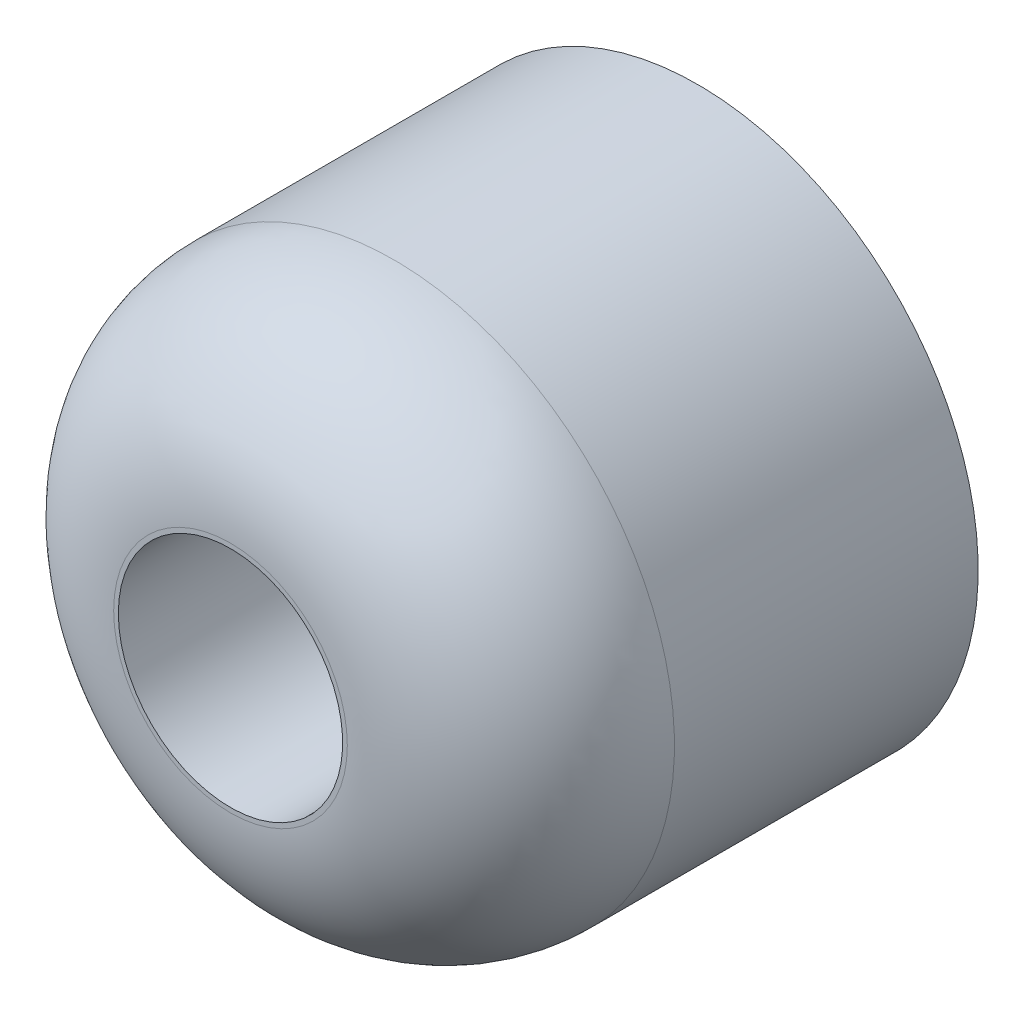
SolidWorks part; units mm, degrees
ref_plane "Front Plane" through (0, 0, 0) normal (0, 0, 1) x (1, 0, 0)
ref_plane "Top Plane" through (0, 0, 0) normal (0, 1, 0) x (1, 0, 0)
ref_plane "Right Plane" through (0, 0, 0) normal (1, 0, 0) x (0, 0, -1)
sketch "Sketch1" plane through (0, 0, 0) normal (1, 0, 0) x (0, 0, -1)
  line L0 (0, 0) -> (-21.5788, 0) construction
  line L1 (0, 2.4) -> (-10, 2.4)
  line L2 (-10, 2.4) -> (-10, 2.5)
  line L3 (-6.5, 6) -> (0, 6)
  line L4 (0, 6) -> (0, 5.5)
  line L5 (0, 5.5) -> (-6, 5.5)
  line L6 (-6, 5.5) -> (-6, 3.9)
  line L7 (-6, 3.9) -> (0, 3.9)
  line L8 (0, 3.9) -> (0, 2.4)
  arc A0 (-6.5, 6) -> (-10, 2.5) centre (-6.5, 2.5) ccw
  point P5 (-21.5788, 0)
  point P14 (-10, 6)
  dimension "D7" = 3.5
  dimension "D1" = 2.4
  dimension "D2" = 3.9
  dimension "D3" = 5.5
  dimension "D4" = 6
  dimension "D5" = 10
  dimension "D6" = 6
revolve "Revolve1" add sketch "Sketch1" angle 360 about L0
